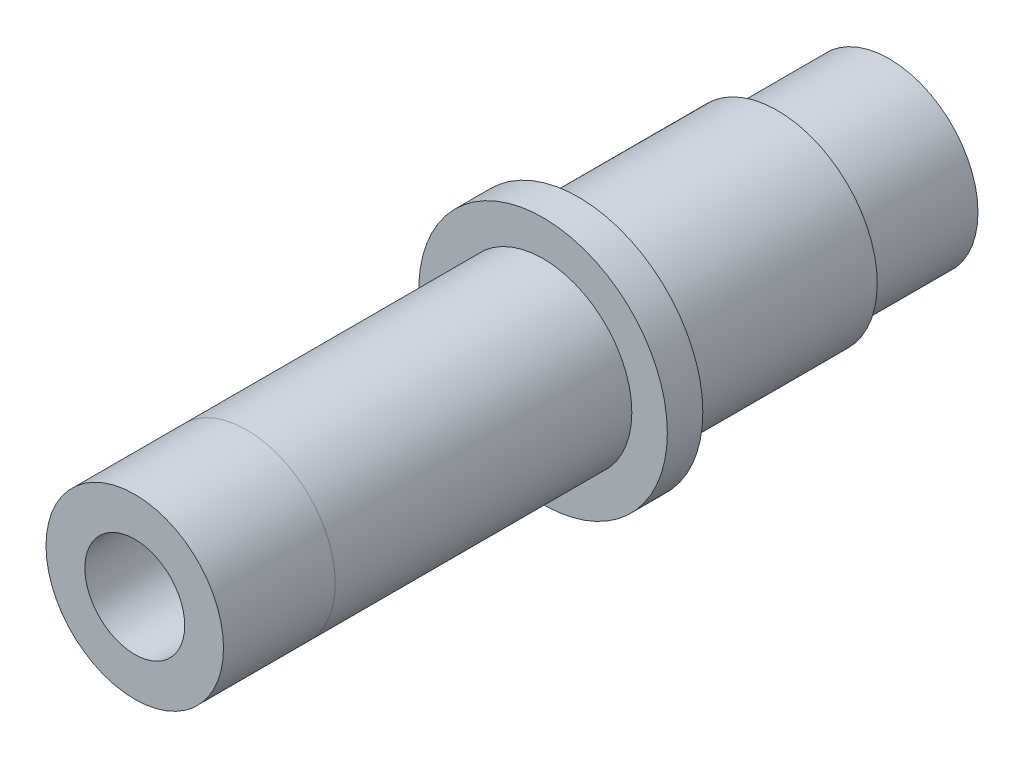
SolidWorks part; units mm, degrees
ref_plane "Front Plane" through (0, 0, 0) normal (0, 0, 1) x (1, 0, 0)
ref_plane "Top Plane" through (0, 0, 0) normal (0, 1, 0) x (1, 0, 0)
ref_plane "Right Plane" through (0, 0, 0) normal (1, 0, 0) x (0, 0, -1)
sketch "Sketch1" plane through (0, 0, 0) normal (0, 0, 1) x (1, 0, 0)
  circle A0 centre (0, 0) radius 6.35
  dimension "D1" = 12.7
extrude "Boss-Extrude1" add sketch "Sketch1" along normal blind 30.48 and the other way blind 23.495 contours A0
sketch "Sketch2" plane through (0, 0, 0) normal (0, 0, 1) x (1, 0, 0)
  circle A0 centre (0, 0) radius 8.89
  dimension "D1" = 17.78
extrude "Boss-Extrude2" add sketch "Sketch2" along normal mid plane 2.54
sketch "Sketch3" plane through (0, 0, 0) normal (1, 0, 0) x (0, 0, -1)
  line L0 (-30.48, 6.35) -> (-30.48, -6.35) construction
  line L1 (-30.48, 6.35) -> (-30.48, -6.35)
  line L2 (-22.48, 6.35) -> (-22.48, -6.35)
  line L3 (23.495, -6.35) -> (23.495, 6.35) construction
  line L6 (15.495, -6.35) -> (15.495, 6.35)
  line L7 (23.495, -6.35) -> (23.495, 6.35)
  dimension "D1" = 8
  dimension "D2" = 8
split line "Split Line1"
sketch "Sketch4" plane through (0, 0, 0) normal (0, 0, 1) x (1, 0, 0)
  circle A0 centre (0, 0) radius 7.1438
  dimension "D1" = 14.2875
extrude "Boss-Extrude3" add sketch "Sketch4" against normal up to vertex (15.495 mm away)
sketch "Sketch5" plane through (0, 0, 30.48) normal (0, 0, 1) x (1, 0, 0)
  circle A0 centre (0, 0) radius 3.5719
  dimension "D1" = 7.1437
extrude "Cut-Extrude1" cut sketch "Sketch5" against normal through all
